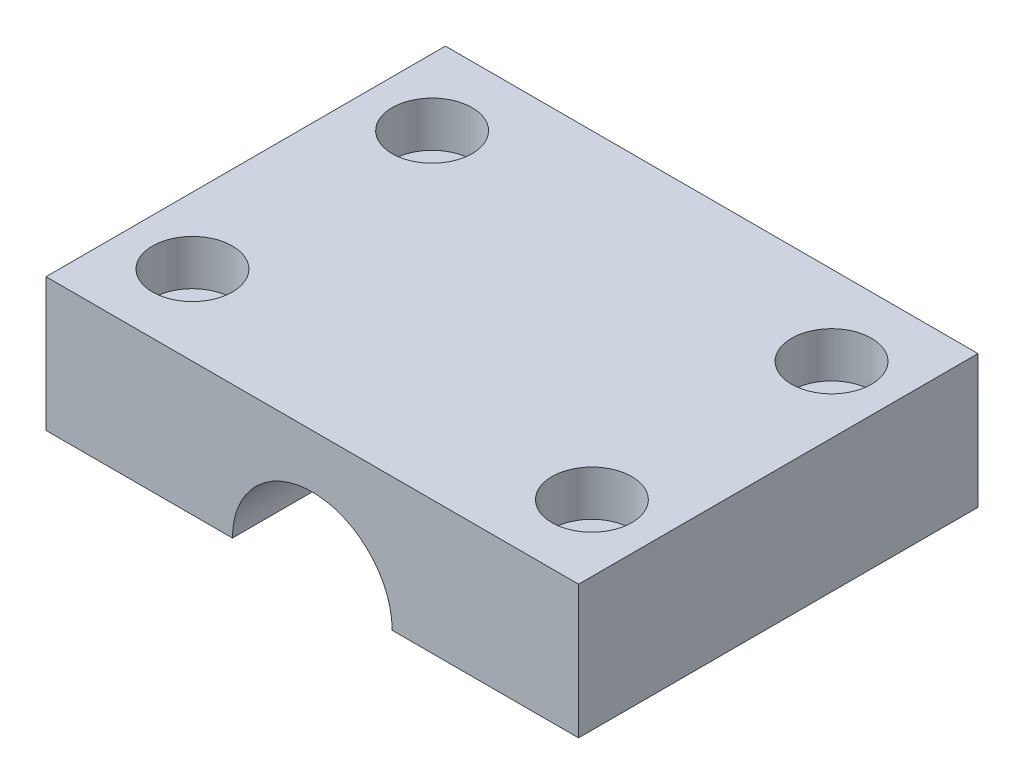
SolidWorks part; units mm, degrees
material "ABS"
ref_plane "前视基准面" through (0, 0, 0) normal (0, 0, 1) x (1, 0, 0)
ref_plane "上视基准面" through (0, 0, 0) normal (0, 1, 0) x (1, 0, 0)
ref_plane "右视基准面" through (0, 0, 0) normal (1, 0, 0) x (0, 0, -1)
other "Configuration Table"
sketch "草图1" plane through (0, 0, 0) normal (0, 1, 0) x (1, 0, 0)
  line L1 (0, 0) -> (40, 0)
  line L2 (0, 0) -> (0, 30)
  line L3 (0, 30) -> (40, 30)
  line L4 (40, 0) -> (40, 30)
  dimension "D1" = 30
  dimension "D2" = 40
extrude "凸台-拉伸1" add sketch "草图1" along normal blind 10
sketch "草图2" plane through (0, 0, 0) normal (0, 0, 1) x (1, 0, 0)
  line L0 (0, 0) -> (40, 0) construction
  line L1 (14, 0) -> (26, 0)
  arc A0 (14, 0) -> (26, 0) centre (20, 0) cw
  dimension "D1" = 6
extrude "切除-拉伸1" cut sketch "草图2" against normal through all
sketch "草图3" plane through (0, 10, 0) normal (0, 1, 0) x (-1, 0, 0)
  line L0 (0, 0) -> (-40, 0) construction
  line L1 (-20, -30) -> (-20, 0) construction
  line L2 (-40, -30) -> (0, -30) construction
  line L3 (-35, -24) -> (-5, -24) construction
  line L4 (-35, -24) -> (-35, -6) construction
  point P0 (-35, -24)
  point P7 (-20, -15)
  point P8 (-5, -24)
  point P11 (-5, -6)
  point P12 (-35, -6)
  dimension "D1" = 9
  dimension "D2" = 15
  dimension "D5" = 30
  dimension "D6" = 18
  dimension "D3" = 2
  dimension "D4" = 2
hole_wizard "M3 六角圆柱头螺钉的柱形沉头孔1" positions "草图3" profile "草图4" counterbore size "M3" standard "GB" end condition through all
sketch "草图4" plane through (35, 10, -24) normal (1, 0, 0) x (0, 0, 1)
  line L0 (0, 0) -> (0, 10)
  line L1 (0, 10) -> (1.6, 10)
  line L3 (1.6, 10) -> (1.6, 3.4)
  line L4 (1.6, 3.4) -> (3, 3.4)
  line L5 (3, 3.4) -> (3, 0)
  line L7 (3, 0) -> (0, 0)
  line L11 (0, -6.35) -> (0, 107.95) construction
  dimension "通孔孔直径" = 3.2
  dimension "通孔孔深度" = 10
  dimension "柱形沉头孔直径" = 6
  dimension "柱形沉头孔深度" = 3.4
